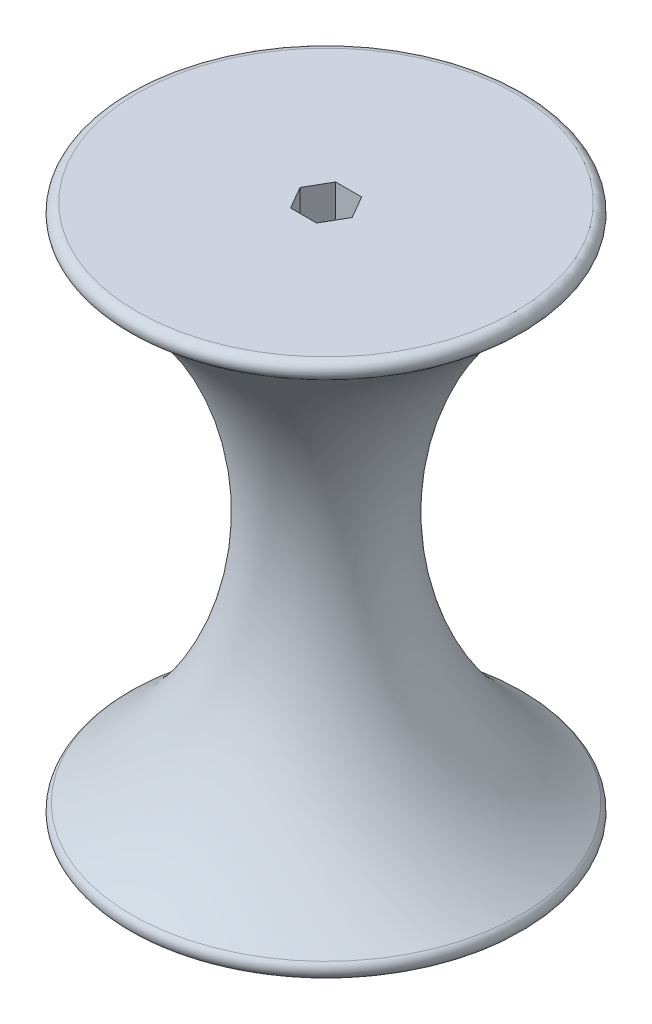
SolidWorks part; units mm, degrees
ref_plane "Front Plane" through (0, 0, 0) normal (0, 0, 1) x (1, 0, 0)
ref_plane "Top Plane" through (0, 0, 0) normal (0, 1, 0) x (1, 0, 0)
ref_plane "Right Plane" through (0, 0, 0) normal (1, 0, 0) x (0, 0, -1)
sketch "Sketch1" plane through (0, 0, 0) normal (0, 0, 1) x (1, 0, 0)
  line L1 (0, -76.2) -> (53.7699, -76.2)
  line L2 (0, -76.2) -> (0, 76.2)
  line L3 (0, 76.2) -> (53.7699, 76.2)
  arc A0 (55.2749, 71.6139) -> (55.2749, -71.6139) centre (107.95, 0) ccw
  arc A1 (55.2749, -71.6139) -> (53.7699, -76.2) centre (53.7699, -73.66) cw
  arc A2 (53.7699, 76.2) -> (55.2749, 71.6139) centre (53.7699, 73.66) cw
  point P0 (0, 0)
  point P10 (19.05, 0)
  point P12 (0, 0)
  dimension "D2" = 88.9
  dimension "D4" = 19.05
  dimension "D3" = 2.54
  dimension "D5" = 152.4
ref_axis "Axis1" through (0, -76.2, 0) along (0, 1, 0)
revolve "Revolve1" add sketch "Sketch1" angle 360 about axis through (0, -76.2, 0) along (0, 1, 0)
sketch "Sketch3" plane through (0, 76.2, 0) normal (0, 1, 0) x (1, 0, 0)
  line L0 (7.4057, 0) -> (3.7028, -6.4135)
  line L1 (3.7028, -6.4135) -> (-3.7028, -6.4135)
  line L2 (-3.7028, -6.4135) -> (-7.4057, 0)
  line L3 (-7.4057, 0) -> (-3.7028, 6.4135)
  line L4 (-3.7028, 6.4135) -> (3.7028, 6.4135)
  line L5 (3.7028, 6.4135) -> (7.4057, 0)
  line L6 (7.4057, 0) -> (-7.4057, 0) construction
  circle A1 centre (0, 0) radius 53.7699
  circle A3 centre (0, 0) radius 53.7699 construction
  point P5 (0, 0)
  dimension "D2" = 12.827
  dimension "D3" = 12.827
  dimension "D1" = 0
extrude "Cut-Extrude1" cut sketch "Sketch3" against normal through all
